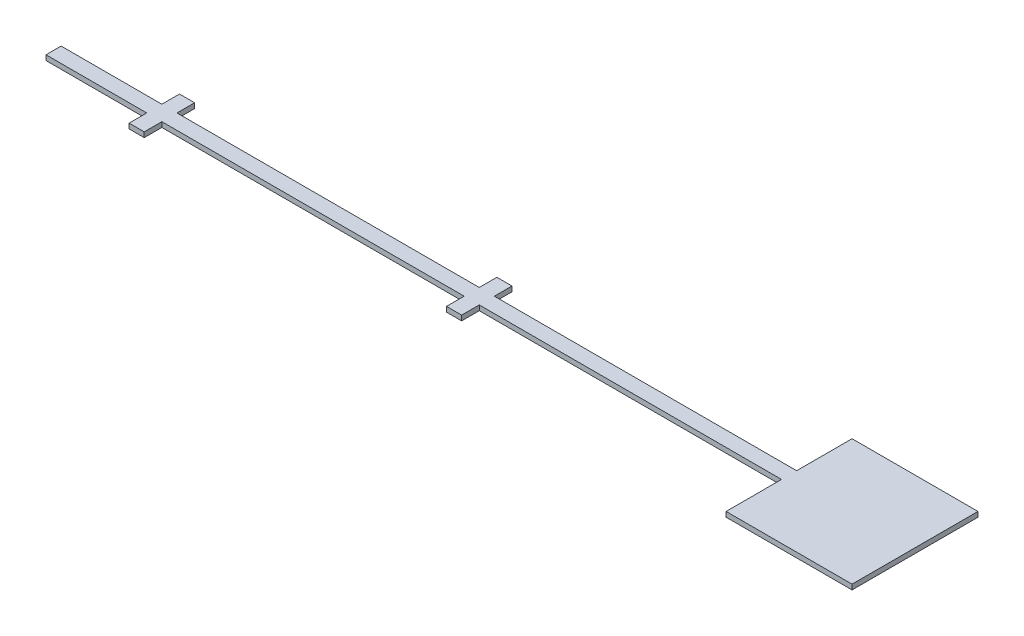
SolidWorks part; units mm, degrees
ref_plane "Front Plane" through (0, 0, 0) normal (0, 0, 1) x (1, 0, 0)
ref_plane "Top Plane" through (0, 0, 0) normal (0, 1, 0) x (1, 0, 0)
ref_plane "Right Plane" through (0, 0, 0) normal (1, 0, 0) x (0, 0, -1)
sketch "Sketch1" plane through (0, 0, 0) normal (0, 1, 0) x (1, 0, 0)
  line L0 (-47.7143, 5.9524) -> (-47.7143, 2.9524)
  line L1 (-47.7143, 2.9524) -> (-27.7143, 2.9524)
  line L2 (-27.7143, 2.9524) -> (-27.7143, -0.5476)
  line L3 (-27.7143, -0.5476) -> (-24.7143, -0.5476)
  line L4 (-24.7143, -0.5476) -> (-24.7143, 2.9524)
  line L5 (-24.7143, 2.9524) -> (35.2857, 2.9524)
  line L6 (35.2857, 2.9524) -> (35.2857, -0.5476)
  line L7 (35.2857, -0.5476) -> (38.2857, -0.5476)
  line L8 (38.2857, -0.5476) -> (38.2857, 2.9524)
  line L9 (38.2857, 2.9524) -> (98.2857, 2.9524)
  line L10 (98.2857, 2.9524) -> (98.2857, -8.0476)
  line L11 (98.2857, -8.0476) -> (123.2857, -8.0476)
  line L12 (123.2857, -8.0476) -> (123.2857, 16.9524)
  line L13 (123.2857, 16.9524) -> (98.2857, 16.9524)
  line L14 (98.2857, 16.9524) -> (98.2857, 5.9524)
  line L15 (98.2857, 5.9524) -> (38.2857, 5.9524)
  line L16 (38.2857, 5.9524) -> (38.2857, 9.4524)
  line L17 (38.2857, 9.4524) -> (35.2857, 9.4524)
  line L18 (35.2857, 9.4524) -> (35.2857, 5.9524)
  line L19 (35.2857, 5.9524) -> (-24.7143, 5.9524)
  line L20 (-24.7143, 5.9524) -> (-24.7143, 9.4524)
  line L21 (-24.7143, 9.4524) -> (-27.7143, 9.4524)
  line L22 (-27.7143, 9.4524) -> (-27.7143, 5.9524)
  line L23 (-27.7143, 5.9524) -> (-47.7143, 5.9524)
  dimension "D1" = 20
  dimension "D2" = 60
  dimension "D3" = 60
  dimension "D4" = 3
  dimension "D5" = 3
  dimension "D6" = 3
  dimension "D7" = 3
  dimension "D8" = 3
  dimension "D9" = 10
  dimension "D10" = 3
  dimension "D11" = 10
  dimension "D12" = 25
  dimension "D13" = 11
  dimension "D14" = 25
  dimension "D15" = 3.5
  dimension "D16" = 3.5
  dimension "D17" = 3.5
  dimension "D18" = 3.5
extrude "Boss-Extrude1" add sketch "Sketch1" along normal blind 1
